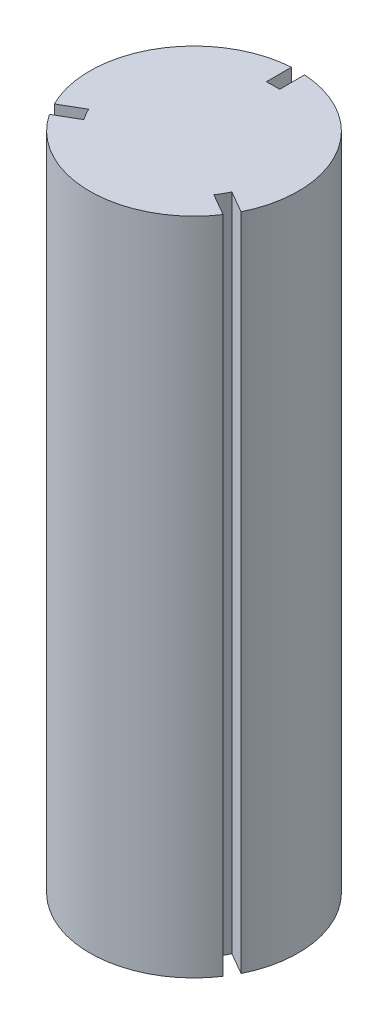
SolidWorks part; units mm, degrees
ref_plane "Front Plane" through (0, 0, 0) normal (0, 0, 1) x (1, 0, 0)
ref_plane "Top Plane" through (0, 0, 0) normal (0, 1, 0) x (1, 0, 0)
ref_plane "Right Plane" through (0, 0, 0) normal (1, 0, 0) x (0, 0, -1)
sketch "Sketch1" plane through (0, 0, 0) normal (0, 1, 0) x (1, 0, 0)
  circle A0 centre (0, 0) radius 3.95
  dimension "D1" = 7.9
extrude "Boss-Extrude1" add sketch "Sketch1" along normal blind 25
sketch "Sketch2" plane through (0, 25, 0) normal (0, 1, 0) x (1, 0, 0)
  line L0 (0.125, 0.2165) -> (3.5389, -1.7545)
  line L1 (-0.25, 0) -> (0.25, 0)
  line L2 (-0.25, 0) -> (-0.25, 3.9421)
  line L3 (-0.25, 3.9421) -> (0.25, 3.9421)
  line L4 (0.25, 0) -> (0.25, 3.9421)
  line L5 (0.125, 0.2165) -> (-0.125, -0.2165)
  line L6 (-0.125, -0.2165) -> (3.2889, -2.1875)
  line L7 (3.5389, -1.7545) -> (3.2889, -2.1875)
  line L8 (0.125, -0.2165) -> (-3.2889, -2.1875)
  line L9 (0.125, -0.2165) -> (-0.125, 0.2165)
  line L10 (-0.125, 0.2165) -> (-3.5389, -1.7545)
  line L11 (-3.2889, -2.1875) -> (-3.5389, -1.7545)
  circle A0 centre (0, 0) radius 3.95 construction
  circle A1 centre (0, 0) radius 3
  point P6 (0, 0)
  point P10 (0, 0)
  point P18 (0, 0)
  dimension "D3" = 6
  dimension "D1" = 0.5
  dimension "D2" = 3
extrude "Cut-Extrude1" cut sketch "Sketch2" against normal blind 25 contours A1 L4 L3 L2 | A1 L10 L11 L8 | A1 L6 L7 L0
